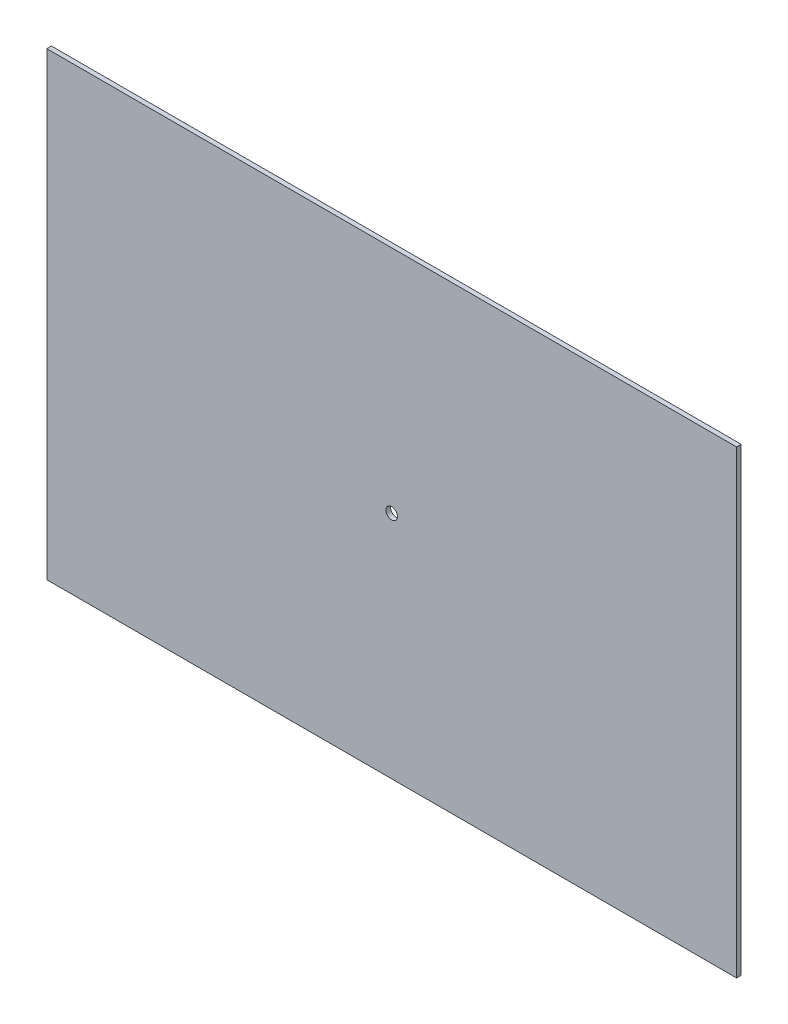
SolidWorks part; units mm, degrees
ref_plane "Спереди" through (0, 0, 0) normal (0, 0, 1) x (1, 0, 0)
ref_plane "Сверху" through (0, 0, 0) normal (0, 1, 0) x (1, 0, 0)
ref_plane "Справа" through (0, 0, 0) normal (1, 0, 0) x (0, 0, -1)
sketch "Эскиз1" plane through (0, 0, 0) normal (0, 0, 1) x (1, 0, 0)
  line L1 (-150, 100) -> (150, 100)
  line L2 (-150, 100) -> (-150, -100)
  line L3 (-150, -100) -> (150, -100)
  line L4 (150, 100) -> (150, -100)
  line L5 (-150, 100) -> (150, -100) construction
  line L6 (-150, -100) -> (150, 100) construction
  point P0 (0, 0)
  dimension "D1" = 300
  dimension "D2" = 200
extrude "Основа" add sketch "Эскиз1" along normal blind 2
sketch "Эскиз2" plane through (0, 0, 2) normal (0, 0, 1) x (1, 0, 0)
  circle A0 centre (0, 0) radius 2.5
  dimension "D1" = 5
extrude "Вырез-Вытянуть1" cut sketch "Эскиз2" against normal through all
